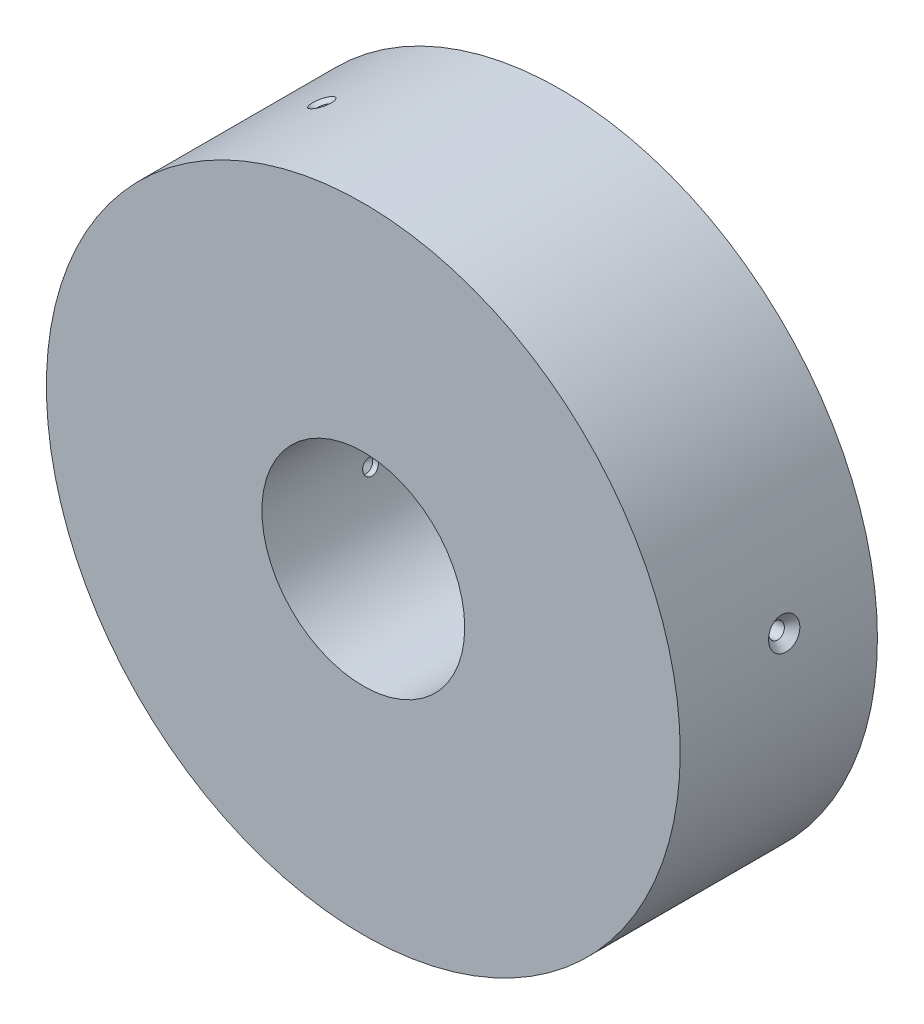
SolidWorks part; units mm, degrees
ref_plane "Front Plane" through (0, 0, 0) normal (0, 0, 1) x (1, 0, 0)
ref_plane "Top Plane" through (0, 0, 0) normal (0, 1, 0) x (1, 0, 0)
ref_plane "Right Plane" through (0, 0, 0) normal (1, 0, 0) x (0, 0, -1)
sketch "Sketch2" plane through (0, 0, 0) normal (0, 0, 1) x (1, 0, 0)
  circle A0 centre (0, 0) radius 45
  circle A1 centre (0, 0) radius 14.4
  dimension "D1" = 90
extrude "Boss-Extrude1" add sketch "Sketch2" along normal blind 28
hole_wizard "CSK for M2 Flat Head Machine Screw2" positions "3DSketch3" profile "Sketch5" countersink size "M2" standard "ANSI Metric"
sketch3d "3DSketch3"
  point P0 (44.5009, 6.6833, 12.7406)
sketch "Sketch5" plane through (44.5009, 6.6833, 12.7406) normal (0, 0, 1) x (-0.1485, 0.9889, 0)
  line L0 (0, 0) -> (0, 60.8609)
  line L1 (0, 60.8609) -> (1.1, 60.2)
  line L2 (1.1, 60.2) -> (1.1, 1.1)
  line L3 (1.1, 1.1) -> (2.2, 0)
  line L5 (2.2, 0) -> (0, 0)
  line L6 (-1.1, 1.1) -> (-2.2, 0) construction
  line L10 (0, 60.8609) -> (-1.1, 60.2) construction
  line L11 (0, -6.35) -> (0, 107.95) construction
  dimension "Hole Dia." = 2.2
  dimension "Hole Depth" = 60.2
  dimension "Near C'Sink Dia." = 4.4
  dimension "Near C'Sink Angle" = 90
  dimension "Drill Angle" = 118
hole_wizard "CSK for #0 Flat Head Machine Screw (100)1" positions "3DSketch4" profile "Sketch6" countersink size "#0" standard "ANSI Inch"
sketch3d "3DSketch4"
  line L0 (0, 0, 28) -> (0, 0, 0) construction
  point P0 (0, 0, 14.1206)
  point P4 (-19.9595, 40.3314, 13.9366)
sketch "Sketch6" plane through (-19.9595, 40.3314, 13.9366) normal (0, 0, 1) x (-0.8963, -0.4435, 0)
  line L0 (0, 0) -> (0, 60.7342)
  line L1 (0, 60.7342) -> (0.889, 60.2)
  line L2 (0.889, 60.2) -> (0.889, 0.5222)
  line L3 (0.889, 0.5222) -> (1.5113, 0)
  line L5 (1.5113, 0) -> (0, 0)
  line L6 (-0.889, 0.5222) -> (-1.5113, 0) construction
  line L10 (0, 60.7342) -> (-0.889, 60.2) construction
  line L11 (0, -6.35) -> (0, 107.95) construction
  dimension "Hole Dia." = 1.778
  dimension "Hole Depth" = 60.2
  dimension "Near C'Sink Dia." = 3.0226
  dimension "Near C'Sink Angle" = 100
  dimension "Drill Angle" = 118
